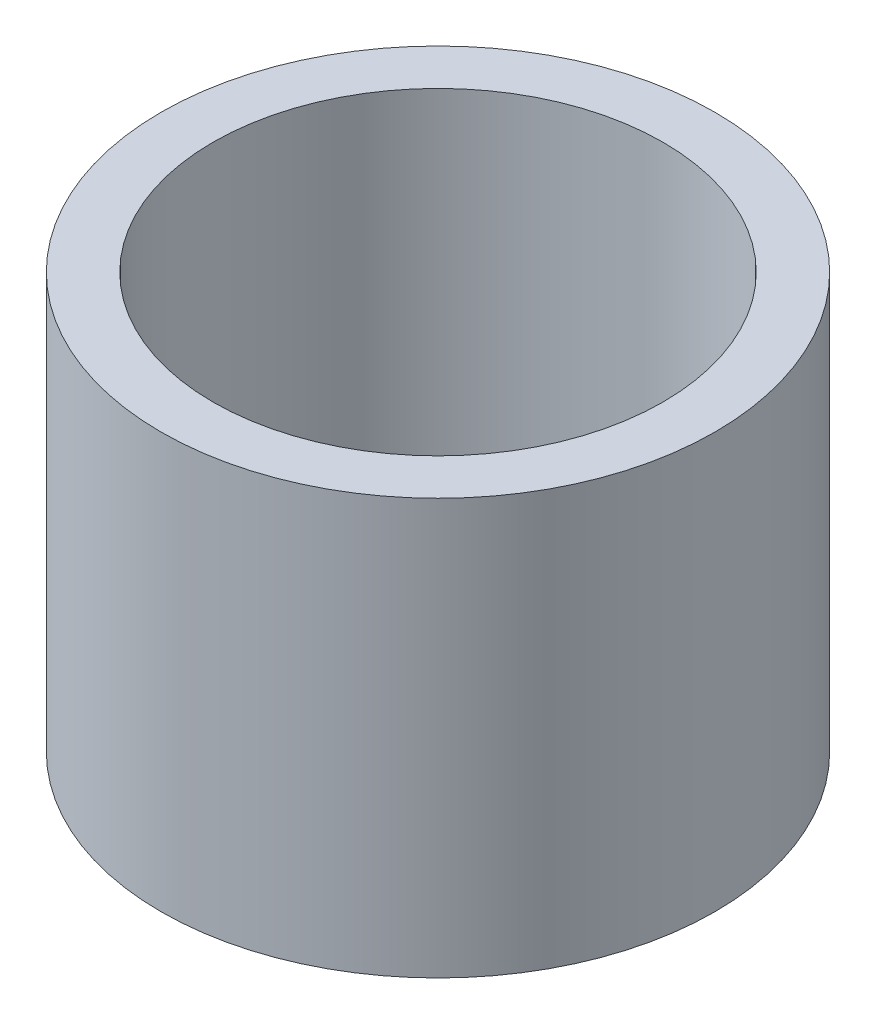
SolidWorks part; units mm, degrees
ref_plane "Front Plane" through (0, 0, 0) normal (0, 0, 1) x (1, 0, 0)
ref_plane "Top Plane" through (0, 0, 0) normal (0, 1, 0) x (1, 0, 0)
ref_plane "Right Plane" through (0, 0, 0) normal (1, 0, 0) x (0, 0, -1)
sketch "Sketch1" plane through (0, 0, 0) normal (0, 1, 0) x (1, 0, 0)
  circle A0 centre (0, 0) radius 32.5
  circle A1 centre (0, 0) radius 40
  dimension "D1" = 65
  dimension "D2" = 80
extrude "Boss-Extrude1" add sketch "Sketch1" along normal blind 60
